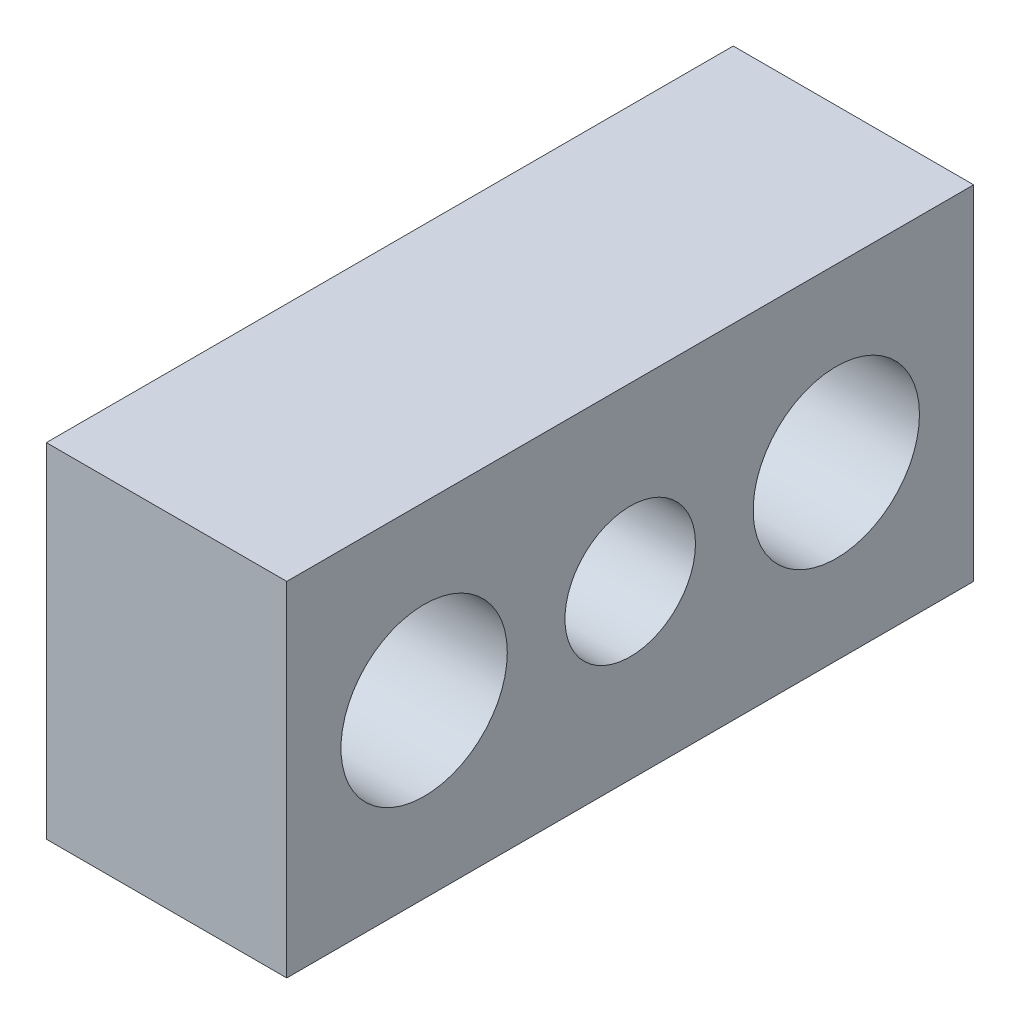
SolidWorks part; units mm, degrees
ref_plane "Front Plane" through (0, 0, 0) normal (0, 0, 1) x (1, 0, 0)
ref_plane "Top Plane" through (0, 0, 0) normal (0, 1, 0) x (1, 0, 0)
ref_plane "Right Plane" through (0, 0, 0) normal (1, 0, 0) x (0, 0, -1)
sketch "Sketch1" plane through (0, 0, 0) normal (1, 0, 0) x (0, 0, -1)
  line L1 (0, 0) -> (20, 0)
  line L2 (0, 0) -> (0, 10)
  line L3 (0, 10) -> (20, 10)
  line L4 (20, 0) -> (20, 10)
  circle A0 centre (10, 5) radius 1.9
  circle A1 centre (16, 5) radius 2.4215
  circle A2 centre (4, 5) radius 2.4215
  point P11 (20, 5)
  point P12 (10, 0)
  dimension "D5" = 3.8
  dimension "D1" = 20
  dimension "D2" = 10
  dimension "D3" = 4
  dimension "D4" = 4
extrude "Boss-Extrude1" add sketch "Sketch1" along normal blind 7
